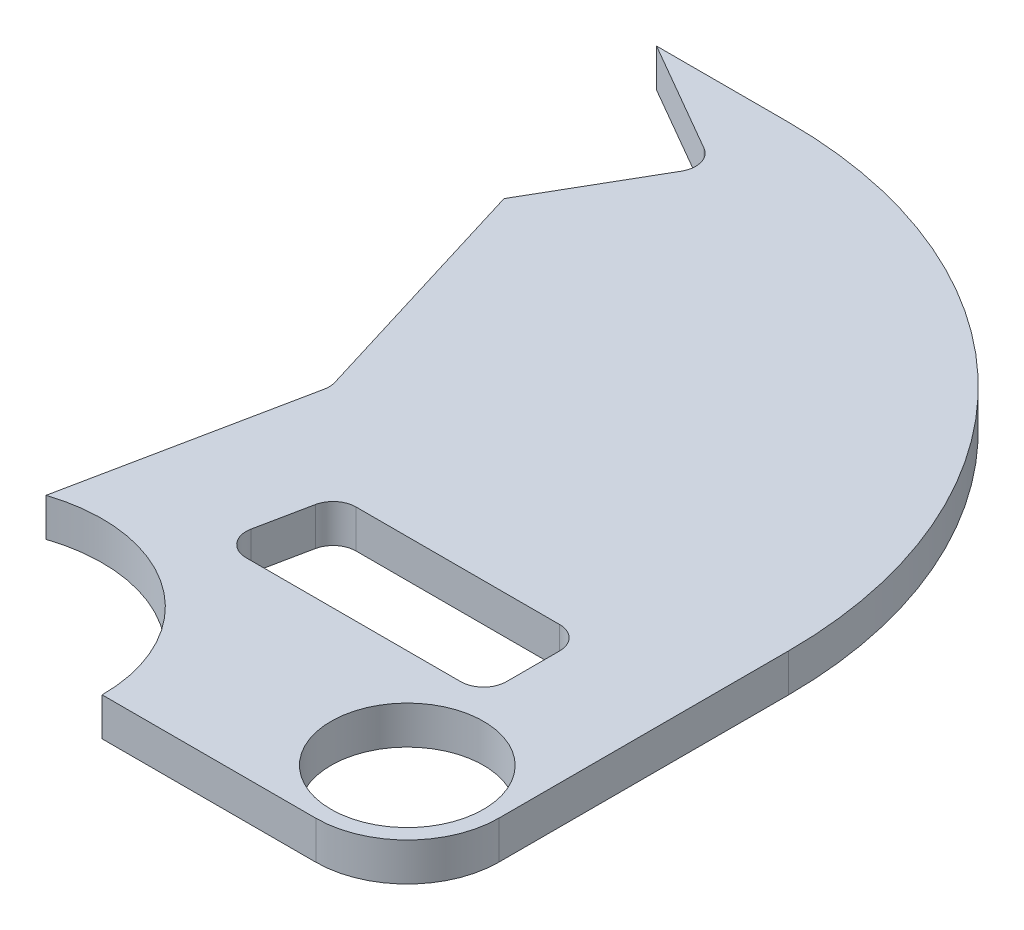
SolidWorks part; units mm, degrees
ref_plane "Front Plane" through (0, 0, 0) normal (0, 0, 1) x (1, 0, 0)
ref_plane "Top Plane" through (0, 0, 0) normal (0, 1, 0) x (1, 0, 0)
ref_plane "Right Plane" through (0, 0, 0) normal (1, 0, 0) x (0, 0, -1)
sketch "Profile Sketch" plane through (0, 0, 0) normal (0, 1, 0) x (1, 0, 0)
  line L0 (0, 60) -> (0, 0) construction
  line L1 (0, 0) -> (60, 0) construction
  line L2 (0, 60) -> (-17.3205, 60)
  line L3 (-17.3205, 60) -> (0, 50)
  line L4 (0, 50) -> (-10, 32.6795)
  line L5 (-10, 32.6795) -> (0, 0)
  line L6 (60, 0) -> (60, -38)
  line L7 (0, 0) -> (-6.3339, -31.0294)
  line L8 (-6.3339, -31.0294) -> (-9.798, -48) construction
  line L9 (48, -50) -> (20, -50)
  line L10 (12.8538, -12.0294) -> (45, -12.0294)
  line L11 (45, -12.0294) -> (45, -25)
  line L12 (45, -25) -> (10.2062, -25)
  line L13 (10.2062, -25) -> (12.8538, -12.0294)
  line L14 (11.53, -18.5147) -> (-3.1669, -15.5147) construction
  line L15 (45, -18.5147) -> (60, -18.5147) construction
  line L16 (28.9269, -12.0294) -> (28.9269, 0) construction
  line L17 (48, -38) -> (60, -38) construction
  line L18 (48, -38) -> (48, -50) construction
  arc A0 (60, 0) -> (0, 60) centre (0, 0) ccw
  arc A1 (20, -50) -> (-6.3339, -31.0294) centre (0, -50) ccw
  circle A2 centre (48, -38) radius 10
  circle A3 centre (0, -50) radius 10 construction
  circle A4 centre (0, -50) radius 20 construction
  arc A6 (48, -50) -> (60, -38) centre (48, -38) ccw
  point P30 (28.9269, -12.0294)
  point P33 (60, -50)
  dimension "D1" = 30
  dimension "D2" = 40
  dimension "D3" = 20
  dimension "D6" = 60
  dimension "D11" = 25
  dimension "D4" = 12
  dimension "D5" = 12
  dimension "D7" = 10
  dimension "D8" = 10
  dimension "D9" = 50
  dimension "D10" = 15
extrude "Profile Extrude" add sketch "Profile Sketch" along normal blind 5
fillet "Trapezoid Fillet" radius 3 4 edges at (45, 2.5, 12.0294) (45, 2.5, 25) (10.2062, 2.5, 25) (12.8538, 2.5, 12.0294)
fillet "Claw Fillet" radius 3 2 edges at (0, 2.5, 0) (0, 2.5, -50)
